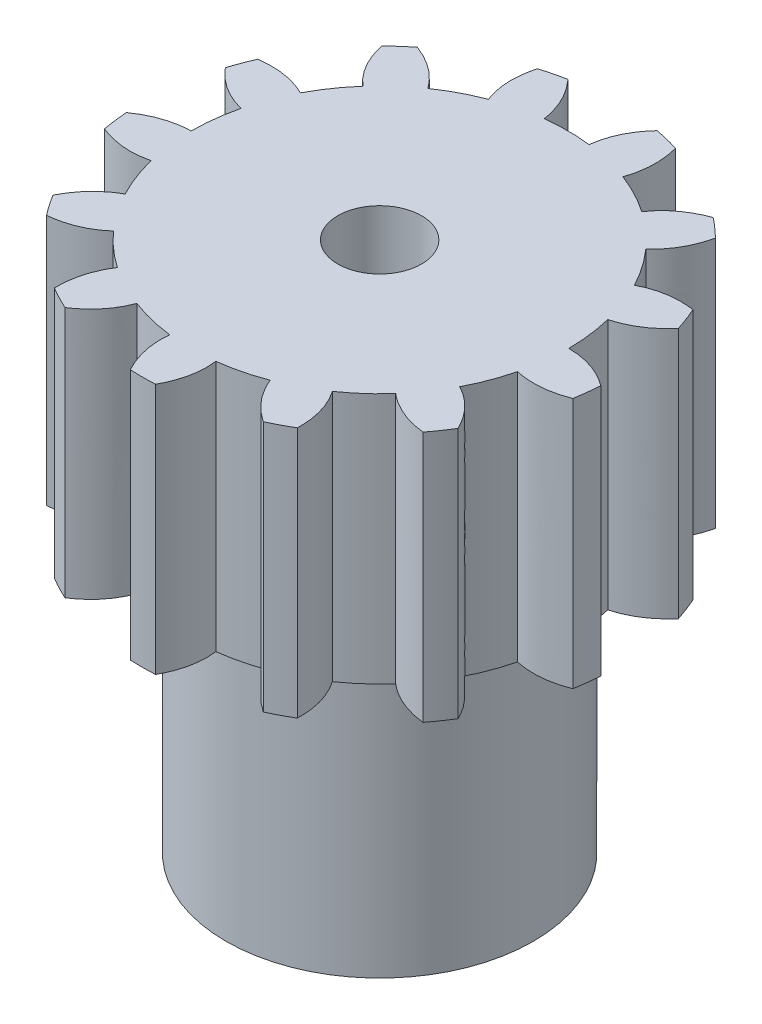
SolidWorks part; units mm, degrees
other "İşaretleme1"
sketch "Çizim1" plane through (16.9627, 17.1442, -16.7035) normal (0.2805, 0.6039, -0.7461) x (-0.8727, 0.484, 0.0636)
material "Dövülebilir Dökme Demir"
ref_plane "Front Plane" through (0, 0, 0) normal (0, 0, 1) x (1, 0, 0)
ref_plane "Top Plane" through (0, 0, 0) normal (0, 1, 0) x (1, 0, 0)
ref_plane "Right Plane" through (0, 0, 0) normal (1, 0, 0) x (0, 0, -1)
sketch "Sketch1" plane through (0, 0, 0) normal (0, 1, 0) x (1, 0, 0)
  line L0 (0, 0) -> (0, 17.0926) construction
  line L1 (0, 0) -> (3.5061, 14.2208) construction
  line L2 (0, 0) -> (1.9234, 15.8361) construction
  line L3 (0, 0) -> (4.6786, 12.3295) construction
  circle A3 centre (0, 0) radius 1.5
  arc A4 (-5.0652, 4.4616) -> (-5.9762, 3.138) centre (0, 0) ccw
  arc A6 (-2.4116, 6.3045) -> (-3.8334, 5.5559) centre (0, 0) ccw
  arc A7 (0.8138, 6.7008) -> (-0.8124, 6.7009) centre (0, 0) ccw
  arc A8 (3.8185, 5.5661) -> (2.3948, 6.3109) centre (0, 0) ccw
  arc A9 (5.9678, 3.154) -> (5.0533, 4.4751) centre (0, 0) ccw
  arc A10 (6.75, 0.0193) -> (6.5542, 1.6141) centre (0, 0) ccw
  arc A11 (5.9858, -3.1198) -> (6.5536, -1.6166) centre (0, 0) ccw
  arc A12 (3.8503, -5.5442) -> (5.0516, -4.477) centre (0, 0) ccw
  arc A13 (0.8328, -6.6984) -> (2.3924, -6.3118) centre (0, 0) ccw
  arc A14 (-2.3755, -6.3182) -> (-0.8149, -6.7006) centre (0, 0) ccw
  arc A15 (-5.0396, -4.4905) -> (-3.8355, -5.5544) centre (0, 0) ccw
  arc A16 (-6.5492, -1.6341) -> (-5.9774, -3.1358) centre (0, 0) ccw
  arc A17 (-6.5585, 1.5966) -> (-6.75, 0.0013) centre (0, 0) ccw
  arc A18 (-7.781, 3.4215) -> (-8.1003, 2.5759) centre (0, 0) ccw
  arc A19 (-8.4797, -0.5864) -> (-8.3695, -1.4836) centre (0, 0) ccw
  arc A20 (-7.2359, -4.46) -> (-6.7214, -5.2032) centre (0, 0) ccw
  arc A21 (-4.3344, -7.3118) -> (-3.5335, -7.7308) centre (0, 0) ccw
  arc A22 (-5.2996, 6.6456) -> (-5.9754, 6.0452) centre (0, 0) ccw
  arc A23 (-1.6043, 8.3472) -> (-2.4816, 8.1297) centre (0, 0) ccw
  arc A24 (8.3737, -1.46) -> (8.4814, -0.5625) centre (0, 0) ccw
  arc A25 (8.093, 2.5987) -> (7.7713, 3.4434) centre (0, 0) ccw
  arc A28 (2.4587, 8.1366) -> (1.5807, 8.3517) centre (0, 0) ccw
  arc A31 (5.9583, 6.062) -> (5.2809, 6.6605) centre (0, 0) ccw
  arc A32 (6.736, -5.1842) -> (7.2485, -4.4396) centre (0, 0) ccw
  arc A33 (3.5553, -7.7208) -> (4.355, -7.2996) centre (0, 0) ccw
  arc A34 (-0.44, -8.4886) -> (0.4639, -8.4873) centre (0, 0) ccw
  spline S0 degree 3 poles (0.633, 5.2117) (0.7252, 5.9828) (1.0144, 6.8191) (1.6201, 7.3229) knots 0 0 0 0 1 1 1 1 construction
  spline S1 degree 1 poles (1.6201, 7.3229) (1.9696, 7.2368) knots 0 0 1 1 construction
  spline S2 degree 3 poles (1.8622, 4.9086) (2.139, 5.6342) (2.2717, 6.5091) (1.9696, 7.2368) knots 0 0 0 0 1 1 1 1 construction
  spline S3 degree 3 poles (3.93, 3.481) (4.5123, 3.9948) (5.0364, 4.7079) (5.1071, 5.4925) knots 0 0 0 0 1 1 1 1 construction
  spline S4 degree 3 poles (2.9825, 4.3206) (3.4225, 4.9605) (4.0672, 5.5666) (4.8376, 5.7313) knots 0 0 0 0 1 1 1 1 construction
  spline S5 degree 1 poles (4.8376, 5.7313) (5.1071, 5.4925) knots 0 0 1 1 construction
  spline S6 degree 3 poles (5.0976, 1.2559) (5.852, 1.4403) (6.6474, 1.8281) (7.0746, 2.49) knots 0 0 0 0 1 1 1 1 construction
  spline S7 degree 3 poles (4.6487, 2.4397) (5.3357, 2.8018) (6.1883, 3.0389) (6.947, 2.8266) knots 0 0 0 0 1 1 1 1 construction
  spline S8 degree 1 poles (6.947, 2.8266) (7.0746, 2.49) knots 0 0 1 1 construction
  spline S9 degree 3 poles (5.0973, -1.2569) (5.851, -1.4442) (6.7355, -1.4705) (7.4214, -1.083) knots 0 0 0 0 1 1 1 1 construction
  spline S10 degree 3 poles (5.25, -0.0002) (6.0266, 0.0012) (6.8917, -0.1851) (7.4648, -0.7256) knots 0 0 0 0 1 1 1 1 construction
  spline S11 degree 1 poles (7.4648, -0.7256) (7.4214, -1.083) knots 0 0 1 1 construction
  spline S12 degree 3 poles (3.9293, -3.4818) (4.5096, -3.9979) (5.2806, -4.4322) (6.068, -4.4078) knots 0 0 0 0 1 1 1 1 construction
  spline S13 degree 3 poles (4.6486, -2.4399) (5.3369, -2.7996) (6.0163, -3.3666) (6.2726, -4.1115) knots 0 0 0 0 1 1 1 1 construction
  spline S14 degree 1 poles (6.2726, -4.1115) (6.068, -4.4078) knots 0 0 1 1 construction
  spline S15 degree 3 poles (1.8612, -4.909) (2.1351, -5.6357) (2.616, -6.3786) (3.3246, -6.7229) knots 0 0 0 0 1 1 1 1 construction
  spline S16 degree 3 poles (2.9822, -4.3208) (3.4245, -4.9591) (3.7626, -5.7769) (3.6434, -6.5556) knots 0 0 0 0 1 1 1 1 construction
  spline S17 degree 1 poles (3.6434, -6.5556) (3.3246, -6.7229) knots 0 0 1 1 construction
  spline S18 degree 3 poles (-0.6334, -5.2117) (-0.7285, -5.9824) (-0.6479, -6.8636) (-0.1805, -7.4978) knots 0 0 0 0 1 1 1 1 construction
  spline S19 degree 3 poles (0.6327, -5.2117) (0.7277, -5.9825) (0.647, -6.8637) (0.1795, -7.4979) knots 0 0 0 0 1 1 1 1 construction
  spline S20 degree 1 poles (0.1795, -7.4979) (-0.1805, -7.4978) knots 0 0 1 1 construction
  spline S21 degree 3 poles (-2.9828, -4.3204) (-3.4252, -4.9586) (-3.7634, -5.7764) (-3.6443, -6.5551) knots 0 0 0 0 1 1 1 1 construction
  spline S22 degree 3 poles (-1.8618, -4.9088) (-2.1359, -5.6354) (-2.6168, -6.3782) (-3.3255, -6.7224) knots 0 0 0 0 1 1 1 1 construction
  spline S23 degree 1 poles (-3.3255, -6.7224) (-3.6443, -6.5551) knots 0 0 1 1 construction
  spline S24 degree 3 poles (-4.6489, -2.4393) (-5.3372, -2.7989) (-6.0167, -3.3658) (-6.2731, -4.1107) knots 0 0 0 0 1 1 1 1 construction
  spline S25 degree 3 poles (-3.9298, -3.4813) (-4.5101, -3.9973) (-5.2812, -4.4315) (-6.0686, -4.407) knots 0 0 0 0 1 1 1 1 construction
  spline S26 degree 1 poles (-6.0686, -4.407) (-6.2731, -4.1107) knots 0 0 1 1 construction
  spline S27 degree 3 poles (-5.25, 0.0006) (-6.0266, 0.0021) (-6.8917, -0.1841) (-7.4649, -0.7246) knots 0 0 0 0 1 1 1 1 construction
  spline S28 degree 3 poles (-5.0975, -1.2563) (-5.8512, -1.4435) (-6.7357, -1.4696) (-7.4215, -1.082) knots 0 0 0 0 1 1 1 1 construction
  spline S29 degree 1 poles (-7.4215, -1.082) (-7.4649, -0.7246) knots 0 0 1 1 construction
  spline S30 degree 3 poles (-4.6484, 2.4403) (-5.3353, 2.8025) (-6.1879, 3.0397) (-6.9466, 2.8276) knots 0 0 0 0 1 1 1 1 construction
  spline S31 degree 3 poles (-5.0974, 1.2566) (-5.8518, 1.441) (-6.6471, 1.829) (-7.0743, 2.4909) knots 0 0 0 0 1 1 1 1 construction
  spline S32 degree 1 poles (-7.0743, 2.4909) (-6.9466, 2.8276) knots 0 0 1 1 construction
  spline S33 degree 3 poles (-2.9819, 4.321) (-3.4218, 4.9609) (-4.0665, 5.5672) (-4.8369, 5.7319) knots 0 0 0 0 1 1 1 1 construction
  spline S34 degree 3 poles (-3.9296, 3.4815) (-4.5118, 3.9954) (-5.0358, 4.7085) (-5.1064, 5.4932) knots 0 0 0 0 1 1 1 1 construction
  spline S35 degree 1 poles (-5.1064, 5.4932) (-4.8369, 5.7319) knots 0 0 1 1 construction
  spline S36 degree 3 poles (-0.6323, 5.2118) (-0.7244, 5.9829) (-1.0135, 6.8193) (-1.6191, 7.3232) knots 0 0 0 0 1 1 1 1 construction
  spline S37 degree 3 poles (-1.8615, 4.9089) (-2.1382, 5.6345) (-2.2708, 6.5094) (-1.9686, 7.237) knots 0 0 0 0 1 1 1 1 construction
  spline S38 degree 1 poles (-1.9686, 7.237) (-1.6191, 7.3232) knots 0 0 1 1 construction
  spline S39 degree 3 poles (-4.6484, 2.4403) (-4.4519, 2.8146) (-4.2099, 3.1651) (-3.9296, 3.4815) knots 0 0 0 0 0.038449 0.038449 0.038449 0.038449 construction
  spline S40 degree 3 poles (-2.9819, 4.321) (-2.6339, 4.5611) (-2.2568, 4.759) (-1.8615, 4.9089) knots 0.076923 0.076923 0.076923 0.076923 0.115372 0.115372 0.115372 0.115372 construction
  spline S41 degree 3 poles (-0.6323, 5.2118) (-0.2126, 5.2627) (0.2133, 5.2627) (0.633, 5.2117) (0.633, 5.2117) knots 0.153846 0.153846 0.153846 0.153846 0.192296 0.192296 0.192296 0.192296 0.192296 construction
  spline S42 degree 3 poles (-5.25, 0.0006) (-5.25, 0.4233) (-5.1986, 0.8461) (-5.0974, 1.2566) knots 0.923077 0.923077 0.923077 0.923077 0.961526 0.961526 0.961526 0.961526 construction
  spline S43 degree 3 poles (-4.6489, -2.4393) (-4.8453, -2.0649) (-4.9963, -1.6667) (-5.0975, -1.2563) knots 0.846154 0.846154 0.846154 0.846154 0.884603 0.884603 0.884603 0.884603 construction
  spline S44 degree 3 poles (-2.9828, -4.3204) (-3.3307, -4.0802) (-3.6494, -3.7977) (-3.9298, -3.4813) knots 0.769231 0.769231 0.769231 0.769231 0.80768 0.80768 0.80768 0.80768 construction
  spline S45 degree 3 poles (-0.6334, -5.2117) (-1.053, -5.1607) (-1.4665, -5.0587) (-1.8618, -4.9088) knots 0.692308 0.692308 0.692308 0.692308 0.730757 0.730757 0.730757 0.730757 construction
  spline S46 degree 3 poles (1.8612, -4.909) (1.4659, -5.0589) (1.0524, -5.1608) (0.6327, -5.2117) knots 0.615385 0.615385 0.615385 0.615385 0.653834 0.653834 0.653834 0.653834 construction
  spline S47 degree 3 poles (3.9293, -3.4818) (3.6489, -3.7982) (3.3302, -4.0806) (2.9822, -4.3208) knots 0.538462 0.538462 0.538462 0.538462 0.576911 0.576911 0.576911 0.576911 construction
  spline S48 degree 3 poles (5.0973, -1.2569) (4.9961, -1.6674) (4.8451, -2.0656) (4.6486, -2.4399) knots 0.461538 0.461538 0.461538 0.461538 0.499988 0.499988 0.499988 0.499988 construction
  spline S49 degree 3 poles (5.0976, 1.2559) (5.1987, 0.8454) (5.25, 0.4226) (5.25, -0.0002) knots 0.384615 0.384615 0.384615 0.384615 0.423065 0.423065 0.423065 0.423065 construction
  spline S50 degree 3 poles (3.93, 3.481) (4.2104, 3.1645) (4.4523, 2.814) (4.6487, 2.4397) knots 0.307692 0.307692 0.307692 0.307692 0.346142 0.346142 0.346142 0.346142 construction
  spline S51 degree 3 poles (1.8622, 4.9086) (2.2575, 4.7587) (2.6345, 4.5607) (2.9825, 4.3206) knots 0.230769 0.230769 0.230769 0.230769 0.269219 0.269219 0.269219 0.269219 construction
  spline S52 degree 3 poles (0.7945, 6.7031) (0.8653, 7.3126) (1.1274, 7.8622) (1.5807, 8.3517) knots 0 0 0 0 0.872429 0.872429 0.872429 0.872429
  spline S53 degree 3 poles (2.4587, 8.1366) (2.623, 7.4967) (2.6017, 6.8881) (2.3948, 6.3109) knots 0.127683 0.127683 0.127683 0.127683 1 1 1 1
  spline S54 degree 3 poles (3.8185, 5.5661) (4.1646, 6.0729) (4.652, 6.4377) (5.2809, 6.6605) knots 0 0 0 0 0.872429 0.872429 0.872429 0.872429
  spline S55 degree 3 poles (5.9583, 6.062) (5.8065, 5.419) (5.5048, 4.89) (5.0533, 4.4751) knots 0.127683 0.127683 0.127683 0.127683 1 1 1 1
  spline S56 degree 3 poles (5.9678, 3.154) (6.5097, 3.4419) (7.1109, 3.5384) (7.7713, 3.4434) knots 0 0 0 0 0.872429 0.872429 0.872429 0.872429
  spline S57 degree 3 poles (8.093, 2.5987) (7.6597, 2.0999) (7.1468, 1.7717) (6.5542, 1.6141) knots 0.127683 0.127683 0.127683 0.127683 1 1 1 1
  spline S58 degree 3 poles (6.75, 0.0193) (7.3636, 0.0224) (7.9407, -0.1715) (8.4814, -0.5625) knots 0 0 0 0 0.872429 0.872429 0.872429 0.872429
  spline S59 degree 3 poles (8.3737, -1.46) (7.7582, -1.7003) (7.1515, -1.7525) (6.5536, -1.6166) knots 0.127683 0.127683 0.127683 0.127683 1 1 1 1
  spline S60 degree 3 poles (5.9858, -3.1198) (6.5306, -3.4022) (6.9515, -3.8421) (7.2485, -4.4396) knots 0 0 0 0 0.872429 0.872429 0.872429 0.872429
  spline S61 degree 3 poles (6.736, -5.1842) (6.0794, -5.1109) (5.5179, -4.8752) (5.0516, -4.477) knots 0.127683 0.127683 0.127683 0.127683 1 1 1 1
  spline S62 degree 3 poles (3.8503, -5.5442) (4.2015, -6.0474) (4.3697, -6.6325) (4.355, -7.2996) knots 0 0 0 0 0.872429 0.872429 0.872429 0.872429
  spline S63 degree 3 poles (3.5553, -7.7208) (3.0079, -7.3508) (2.6202, -6.8811) (2.3924, -6.3118) knots 0.127683 0.127683 0.127683 0.127683 1 1 1 1
  spline S64 degree 3 poles (0.8328, -6.6984) (0.9098, -7.3072) (0.7869, -7.9035) (0.4639, -8.4873) knots 0 0 0 0 0.872429 0.872429 0.872429 0.872429
  spline S65 degree 3 poles (-0.44, -8.4886) (-0.7527, -7.9066) (-0.8777, -7.3106) (-0.8149, -6.7006) knots 0.127683 0.127683 0.127683 0.127683 1 1 1 1
  spline S66 degree 3 poles (-2.3755, -6.3182) (-2.5902, -6.8931) (-2.9762, -7.3639) (-3.5335, -7.7308) knots 0 0 0 0 0.872429 0.872429 0.872429 0.872429
  spline S67 degree 3 poles (-4.3344, -7.3118) (-4.3409, -6.6511) (-4.1746, -6.0653) (-3.8355, -5.5544) knots 0.127683 0.127683 0.127683 0.127683 1 1 1 1
  spline S68 degree 3 poles (-5.0396, -4.4905) (-5.4969, -4.8998) (-6.0575, -5.1373) (-6.7214, -5.2032) knots 0 0 0 0 0.872429 0.872429 0.872429 0.872429
  spline S69 degree 3 poles (-7.2359, -4.46) (-6.9346, -3.872) (-6.5151, -3.4306) (-5.9774, -3.1358) knots 0.127683 0.127683 0.127683 0.127683 1 1 1 1
  spline S70 degree 3 poles (-6.5492, -1.6341) (-7.1443, -1.784) (-7.751, -1.7338) (-8.3695, -1.4836) knots 0 0 0 0 0.872429 0.872429 0.872429 0.872429
  spline S71 degree 3 poles (-8.4797, -0.5864) (-7.9397, -0.2058) (-7.3631, -0.0099) (-6.75, 0.0013) knots 0.127683 0.127683 0.127683 0.127683 1 1 1 1
  spline S72 degree 3 poles (-6.5585, 1.5966) (-7.155, 1.7405) (-7.669, 2.0669) (-8.1003, 2.5759) knots 0 0 0 0 0.872429 0.872429 0.872429 0.872429
  spline S73 degree 3 poles (-7.781, 3.4215) (-7.1259, 3.5075) (-6.5243, 3.413) (-5.9762, 3.138) knots 0.127683 0.127683 0.127683 0.127683 1 1 1 1
  spline S74 degree 3 poles (-5.0652, 4.4616) (-5.5266, 4.8662) (-5.83, 5.3941) (-5.9754, 6.0452) knots 0 0 0 0 0.872429 0.872429 0.872429 0.872429
  spline S75 degree 3 poles (-5.2996, 6.6456) (-4.6796, 6.4173) (-4.1909, 6.0541) (-3.8334, 5.5559) knots 0.127683 0.127683 0.127683 0.127683 1 1 1 1
  spline S76 degree 3 poles (-2.4116, 6.3045) (-2.6321, 6.8771) (-2.6555, 7.4855) (-2.4816, 8.1297) knots 0 0 0 0 0.872429 0.872429 0.872429 0.872429
  spline S77 degree 3 poles (-1.6043, 8.3472) (-1.1613, 7.857) (-0.8973, 7.3082) (-0.8124, 6.7009) knots 0.127683 0.127683 0.127683 0.127683 1 1 1 1
  point P62 (1.792, 8.5633)
  point P64 (0, 0)
  point P66 (2.3745, 8.4197)
  point P121 (0, 0)
  dimension "D2" = 13.5
  dimension "D3" = 0.31
  dimension "D4" = 3
  dimension "D9" = 17
  dimension "D5" = 13.85
  dimension "D6" = 6.925
  dimension "D7" = 6.93
  dimension "D8" = 0.6
extrude "Boss-Extrude1" add sketch "Sketch1" along normal blind 9
sketch "Sketch2" plane through (0, 0, 0) normal (0, -1, 0) x (1, 0, 0)
  circle A1 centre (0, 0) radius 5.5
  dimension "D1" = 11
extrude "Boss-Extrude2" add sketch "Sketch2" along normal blind 10
scale "Ölçek2" bodies to scale 105 scale about centroid uniform scaling yes scale factor 2
